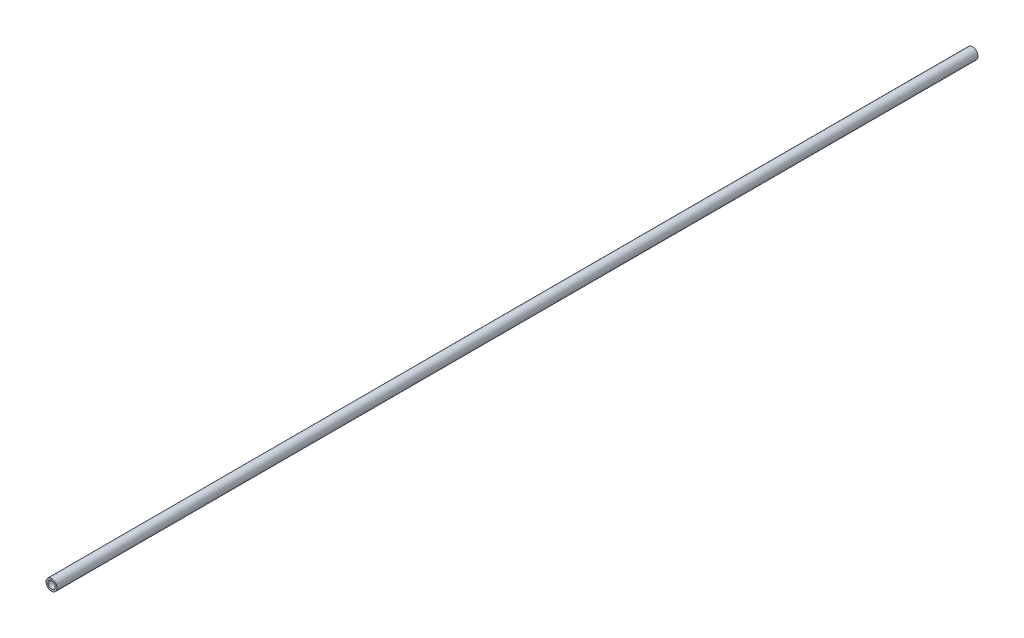
SolidWorks part; units mm, degrees
ref_plane "Спереди" through (0, 0, 0) normal (0, 0, 1) x (1, 0, 0)
ref_plane "Сверху" through (0, 0, 0) normal (0, 1, 0) x (1, 0, 0)
ref_plane "Справа" through (0, 0, 0) normal (1, 0, 0) x (0, 0, -1)
sketch "Эскиз1" plane through (0, 0, 0) normal (0, 0, 1) x (1, 0, 0)
  circle A0 centre (0, 0) radius 2
  circle A1 centre (0, 0) radius 3
  dimension "D1" = 6
  dimension "D2" = 4
extrude "Бобышка-Вытянуть1" add sketch "Эскиз1" along normal blind 500
